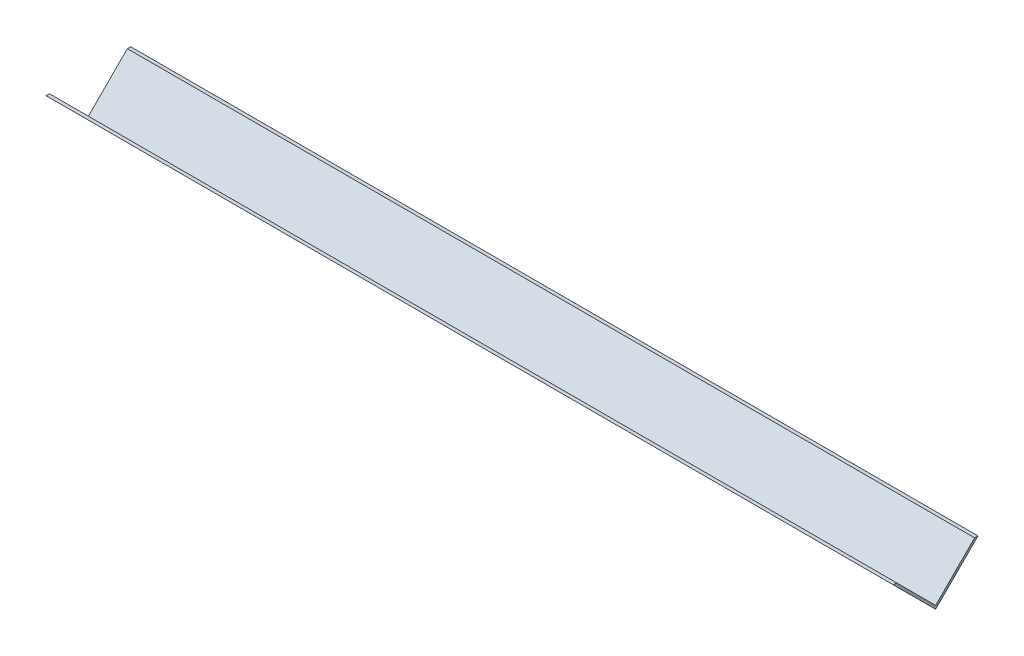
SolidWorks part; units mm, degrees
ref_plane "Alzado" through (0, 0, 0) normal (0, 0, 1) x (1, 0, 0)
ref_plane "Planta" through (0, 0, 0) normal (0, 1, 0) x (1, 0, 0)
ref_plane "Vista lateral" through (0, 0, 0) normal (1, 0, 0) x (0, 0, -1)
sketch "Croquis1" plane through (0, 0, 0) normal (1, 0, 0) x (0, 0, -1)
  line L0 (0, 0) -> (0, 26.816) construction
  line L1 (0, 0) -> (-20, 20)
  line L2 (-20, 20) -> (-18.4052, 20)
  line L3 (-18.4052, 20) -> (0, 1.5948)
  line L4 (18.4052, 20) -> (0, 1.5948)
  line L5 (20, 20) -> (18.4052, 20)
  line L6 (0, 0) -> (20, 20)
  dimension "D1" = 45
  dimension "D2" = 20
extrude "Saliente-Extruir1" add sketch "Croquis1" along normal blind 400
